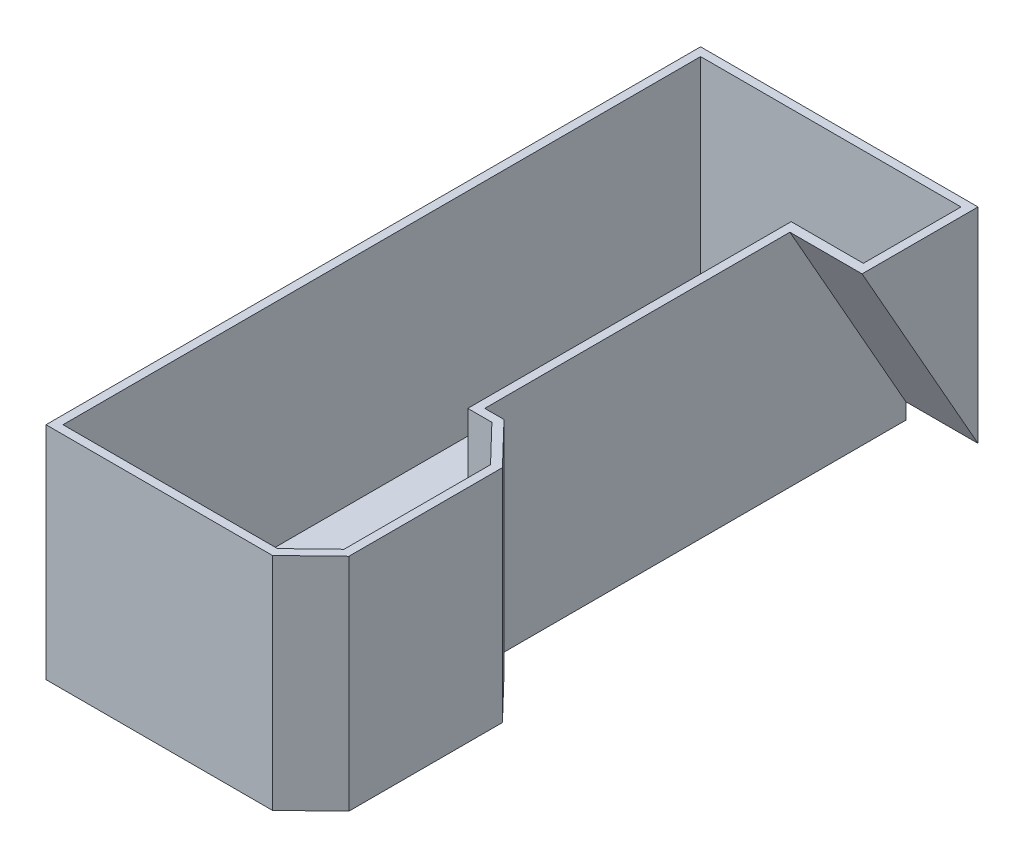
SolidWorks part; units mm, degrees
ref_plane "前视基准面" through (0, 0, 0) normal (0, 0, 1) x (1, 0, 0)
ref_plane "上视基准面" through (0, 0, 0) normal (0, 1, 0) x (1, 0, 0)
ref_plane "右视基准面" through (0, 0, 0) normal (1, 0, 0) x (0, 0, -1)
other "Configuration Table"
sketch "草图1" plane through (0, 0, 0) normal (0, 1, 0) x (1, 0, 0)
  line L1 (0, 0) -> (290, 0)
  line L2 (0, 0) -> (0, 925)
  line L3 (0, 925) -> (290, 925)
  line L4 (290, 0) -> (290, 925)
  dimension "D1" = 925
  dimension "D2" = 290
extrude "凸台-拉伸1" add sketch "草图1" along normal blind 12
sketch "草图3" plane through (0, 12, 0) normal (0, 1, 0) x (1, 0, 0)
  line L0 (290, 0) -> (290, 925) construction
  line L1 (290, 330) -> (317.1818, 330)
  line L2 (290, 330) -> (290, 0)
  line L3 (290, 0) -> (320, 0)
  line L4 (375, 270) -> (375, 53)
  line L5 (317.1818, 330) -> (375, 270)
  line L6 (375, 53) -> (320, 0)
  line L7 (0, 0) -> (290, 0) construction
  dimension "D1" = 330
  dimension "D2" = 0
  dimension "D3" = 30
  dimension "D4" = 85
  dimension "D5" = 60
  dimension "D6" = 217
extrude "凸台-拉伸3" add sketch "草图3" against normal blind 12
sketch "草图4" plane through (0, 12, 0) normal (0, 1, 0) x (1, 0, 0)
  line L16 (12, 913) -> (12, 12)
  line L17 (12, 12) -> (315.1591, 12)
  line L18 (315.1591, 12) -> (363, 58.1012)
  line L19 (363, 58.1012) -> (363, 265.1591)
  line L20 (363, 265.1591) -> (312.0806, 318)
  line L21 (312.0806, 318) -> (278, 318)
  line L22 (278, 318) -> (278, 913)
  line L23 (278, 913) -> (12, 913)
  line L24 (12, 913) -> (12, 12)
  line L25 (12, 12) -> (315.1591, 12)
  line L26 (315.1591, 12) -> (363, 58.1012)
  line L27 (363, 58.1012) -> (363, 265.1591)
  line L28 (363, 265.1591) -> (312.0806, 318)
  line L29 (312.0806, 318) -> (278, 318)
  line L30 (278, 318) -> (278, 913)
  line L31 (278, 913) -> (12, 913)
  line L40 (0, 925) -> (0, 0)
  line L41 (0, 0) -> (320, 0)
  line L42 (320, 0) -> (375, 53)
  line L43 (375, 53) -> (375, 270)
  line L44 (375, 270) -> (317.1818, 330)
  line L45 (317.1818, 330) -> (290, 330)
  line L46 (290, 330) -> (290, 925)
  line L47 (290, 925) -> (0, 925)
  line L48 (0, 925) -> (0, 0)
  line L49 (0, 0) -> (320, 0)
  line L50 (320, 0) -> (375, 53)
  line L51 (375, 53) -> (375, 270)
  line L52 (375, 270) -> (317.1818, 330)
  line L53 (317.1818, 330) -> (290, 330)
  line L54 (290, 330) -> (290, 925)
  line L55 (290, 925) -> (0, 925)
  dimension "D1" = 12
  dimension "D2" = 0
extrude "凸台-拉伸4" add sketch "草图4" along normal blind 300
sketch "草图5" plane through (290, 0, 0) normal (1, 0, 0) x (0, 0, -1)
  line L0 (775, 312) -> (925, 47)
  line L1 (330, 312) -> (925, 312) construction
  line L2 (925, 47) -> (925, 312)
  line L3 (925, 312) -> (775, 312)
  dimension "D1" = 150
  dimension "D2" = 265
extrude "切除-拉伸1" cut sketch "草图5" against normal blind 12
sketch "草图7" plane through (290, 0, 0) normal (1, 0, 0) x (0, 0, -1)
  line L0 (775, 312) -> (925, 47)
  line L1 (925, 47) -> (925, 22.6394)
  line L2 (925, 47) -> (925, 0) construction
  line L3 (925, 22.6394) -> (761.211, 312)
  line L4 (330, 312) -> (775, 312) construction
  line L5 (761.211, 312) -> (775, 312)
  dimension "D1" = 12
extrude "凸台-拉伸5" add sketch "草图7" along normal blind 90
sketch "草图8" plane through (278, 0, 0) normal (1, 0, 0) x (0, 0, -1)
  line L0 (925, 312) -> (925, 47)
  line L1 (925, 47) -> (913, 68.2)
  line L2 (775, 312) -> (925, 47) construction
  line L3 (913, 312) -> (913, 12) construction
  line L4 (913, 68.2) -> (913, 312)
  line L5 (913, 312) -> (925, 312)
extrude "凸台-拉伸6" add sketch "草图8" along normal blind 102
sketch "草图9" plane through (380, 0, 0) normal (1, 0, 0) x (0, 0, -1)
  line L0 (761.211, 312) -> (925, 312)
  line L1 (925, 312) -> (925, 22.6394)
  line L2 (925, 22.6394) -> (925, 312) construction
  line L3 (761.211, 312) -> (925, 22.6394) construction
  line L4 (925, 22.6394) -> (761.211, 312)
extrude "凸台-拉伸7" add sketch "草图9" along normal blind 12
equation "\"D2@草图1\"=220+70"
equation "\"D1@凸台-拉伸6\"=90+12"
